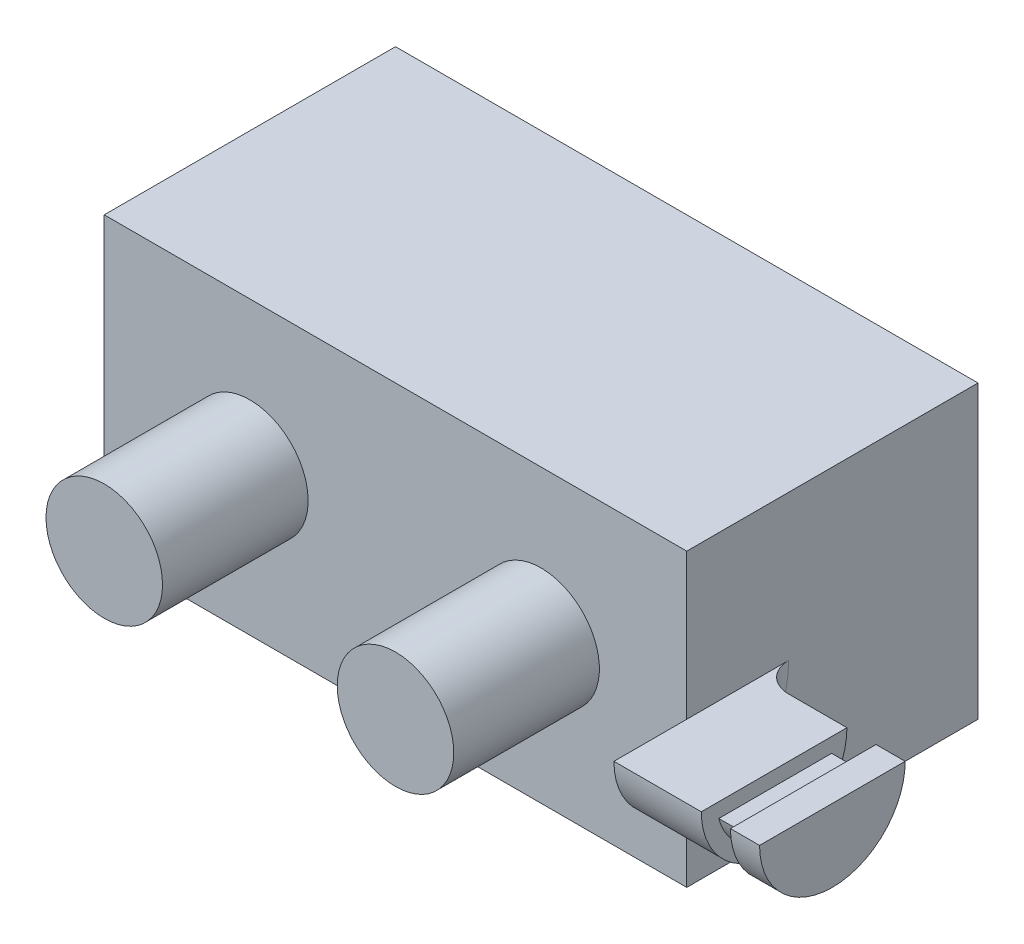
SolidWorks part; units mm, degrees
ref_plane "Front Plane" through (0, 0, 0) normal (0, 0, 1) x (1, 0, 0)
ref_plane "Top Plane" through (0, 0, 0) normal (0, 1, 0) x (1, 0, 0)
ref_plane "Right Plane" through (0, 0, 0) normal (1, 0, 0) x (0, 0, -1)
sketch "Sketch1" plane through (0, 0, 0) normal (0, 1, 0) x (1, 0, 0)
  line L1 (0, 0) -> (50.8, 0)
  line L2 (0, 0) -> (0, 25.4)
  line L3 (0, 25.4) -> (50.8, 25.4)
  line L4 (50.8, 0) -> (50.8, 25.4)
  dimension "D1" = 50.8
  dimension "D2" = 25.4
extrude "Boss-Extrude2" add sketch "Sketch1" along normal blind 25.4
sketch "Sketch3" plane through (0, 0, 0) normal (0, 0, 1) x (1, 0, 0)
  circle A0 centre (12.7, 12.7) radius 5.08
  circle A1 centre (38.1, 12.7) radius 5.08
extrude "Boss-Extrude3" add sketch "Sketch3" along normal blind 12.7
sketch "Sketch4" plane through (0, 0, 0) normal (1, 0, 0) x (0, 0, -1)
  line L1 (-6.35, 12.7) -> (6.35, 12.7)
  arc A1 (-6.35, 12.7) -> (6.35, 12.7) centre (0, 12.7) ccw
  point P3 (0, 12.7)
extrude "Boss-Extrude4" add sketch "Sketch4" along normal blind 12.7 from surface at 50.8 starting at face at (50.8, 12.7, -12.7)
sketch "Sketch24" plane through (0, 0, 0) normal (1, 0, 0) x (0, 0, -1)
  line L2 (6.35, 12.7) -> (-6.35, 12.7) construction
  line L3 (-6.35, 12.7) -> (6.35, 12.7)
  line L5 (-4.8249, 11.43) -> (5.0125, 11.43)
  arc A3 (-4.8249, 11.43) -> (5.0125, 11.43) centre (0.0938, 12.7) ccw
  arc A4 (-6.35, 12.7) -> (6.35, 12.7) centre (0, 12.7) ccw
  point P2 (0, 0)
  point P6 (0, 12.7)
extrude "Cut-Extrude1" cut sketch "Sketch24" against normal blind 2.54 from offset 60.96
fillet "Fillet8" radius 2.54 1 edges at (50.8, 8.2099, -4.4901)
